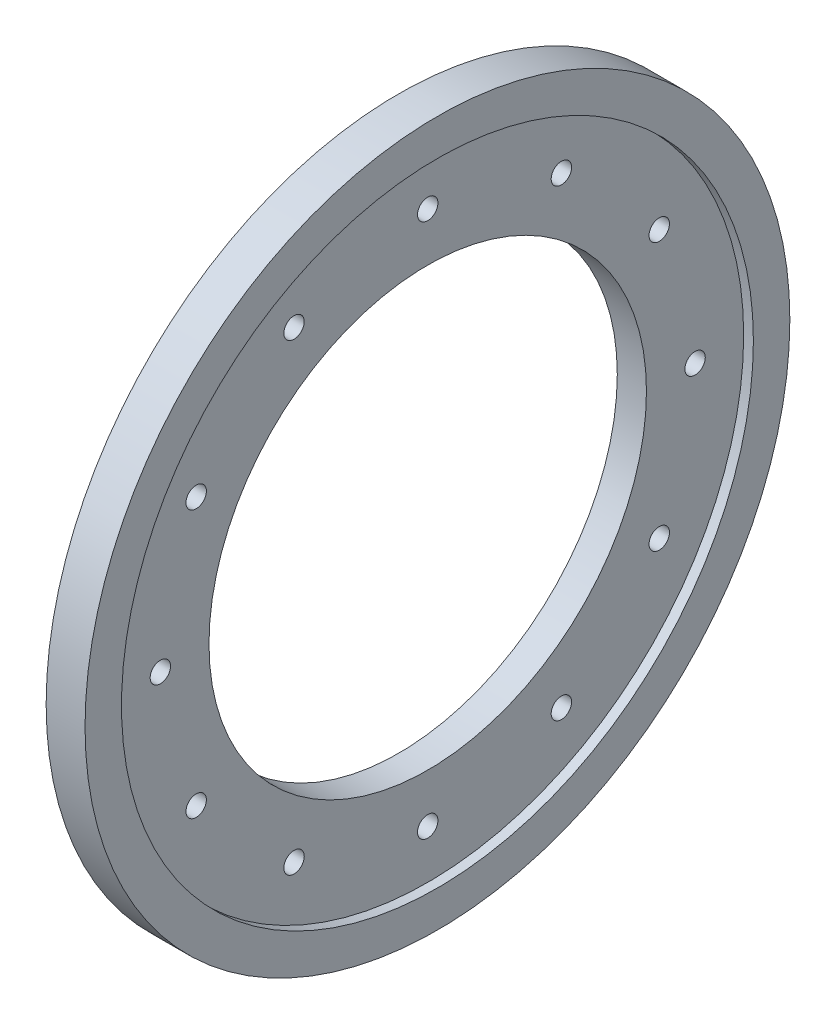
SolidWorks part; units mm, degrees
ref_plane "Front Plane" through (0, 0, 0) normal (0, 0, 1) x (1, 0, 0)
ref_plane "Top Plane" through (0, 0, 0) normal (0, 1, 0) x (1, 0, 0)
ref_plane "Right Plane" through (0, 0, 0) normal (1, 0, 0) x (0, 0, -1)
ref_plane "Plane1" through (0, 0, 0) normal (0, 0, -1) x (-1, 0, 0)
sketch "Sketch1" plane through (0, 0, 0) normal (0, 0, -1) x (-1, 0, 0)
  line L0 (-4, 145) -> (-4, 0)
  line L1 (-4, 0) -> (12, 0)
  line L2 (12, 0) -> (12, 145)
  line L3 (12, 145) -> (-4, 145)
  line L4 (-4, 0) -> (12, 0) construction
revolve "Revolve1" add sketch "Sketch1" angle 360 about L4
hole_wizard "Hole1" positions "Sketch3" profile "Sketch2" legacy
sketch "Sketch3" plane through (4, 0, 0) normal (1, 0, 0) x (0, 0, -1)
  point P0 (0, 0)
sketch "Sketch2" plane through (4, 0, 0) normal (0, 1, 0) x (0, 0, -1)
  line L0 (0, 0) -> (0, 16)
  line L1 (0, 16) -> (90, 16)
  line L2 (90, 16) -> (90, 4)
  line L3 (90, 4) -> (130, 4)
  line L4 (130, 4) -> (130, 0)
  line L5 (130, 0) -> (0, 0)
  line L6 (0, 110) -> (0, -10) construction
  dimension "Diameter" = 180
  dimension "Depth" = 16
  dimension "C-Bore Diameter" = 260
  dimension "C-Bore Depth" = 4
hole_wizard "Ø8.4 (8.4) Diameter Hole1" positions "Sketch5" profile "Sketch4" hole size "Ø8.4" standard "ANSI Metric"
sketch "Sketch5" plane through (0, 0, 0) normal (1, 0, 0) x (0, 0, -1)
  point P0 (110, 0)
  point P1 (95.2628, 55)
  point P2 (55, 95.2628)
  point P3 (0, 110)
  point P4 (-55, 95.2628)
  point P5 (-95.2628, 55)
  point P6 (-110, 0)
  point P7 (-95.2628, -55)
  point P8 (-55, -95.2628)
  point P9 (0, -110)
  point P10 (55, -95.2628)
  point P11 (95.2628, -55)
sketch "Sketch4" plane through (0, 0, -110) normal (0, 1, 0) x (0, 0, -1)
  line L0 (0, 0) -> (0, 12)
  line L1 (0, 12) -> (4.2, 12)
  line L2 (4.2, 12) -> (4.2, 0)
  line L5 (4.2, 0) -> (0, 0)
  line L11 (0, -6.35) -> (0, 107.95) construction
  dimension "Thru Hole Dia." = 8.4
  dimension "Thru Hole Depth" = 12
